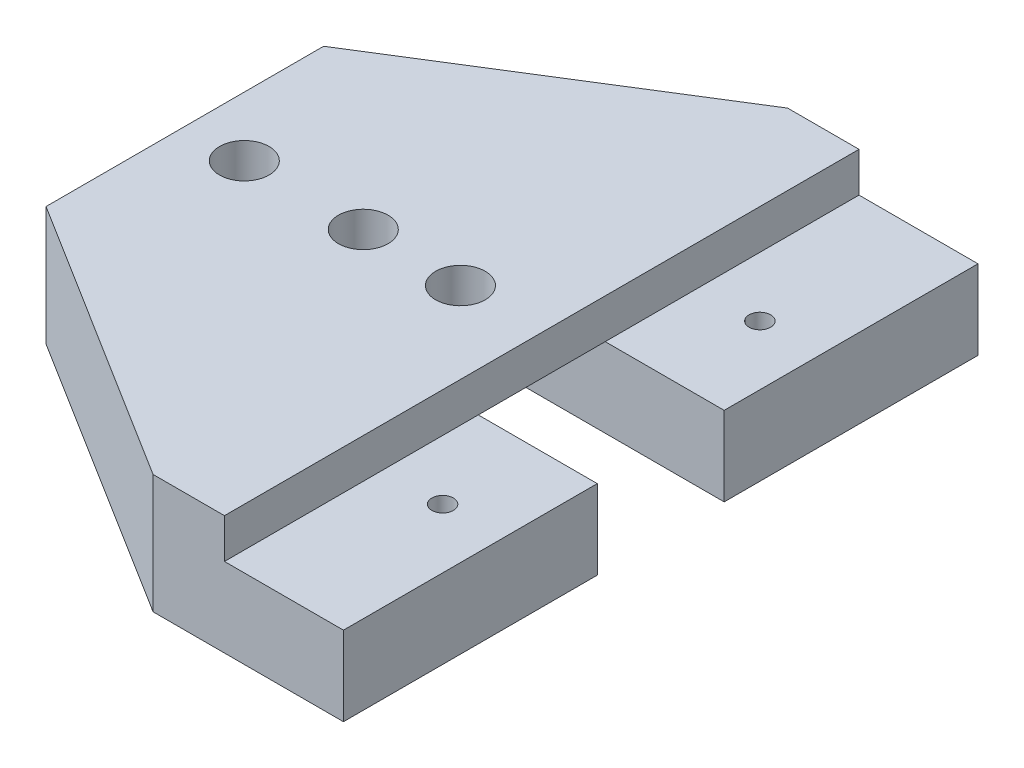
SolidWorks part; units mm, degrees
ref_plane "Front" through (0, 0, 0) normal (0, 0, 1) x (1, 0, 0)
ref_plane "Top" through (0, 0, 0) normal (0, 1, 0) x (1, 0, 0)
ref_plane "Right" through (0, 0, 0) normal (1, 0, 0) x (0, 0, -1)
sketch "Sketch1" plane through (0, 0, 0) normal (0, 1, 0) x (1, 0, 0)
  line L0 (-60.96, 22.225) -> (-60.96, -22.225)
  line L1 (-60.96, -22.225) -> (-15.24, -50.8)
  line L2 (-15.24, -50.8) -> (15.24, -50.8)
  line L3 (15.24, -50.8) -> (15.24, 50.8)
  line L4 (15.24, 50.8) -> (-15.24, 50.8)
  line L5 (-15.24, 50.8) -> (-60.96, 22.225)
  line L6 (-50, 0) -> (50, 0) construction
  line L7 (0, -50) -> (0, 50) construction
  point P6 (-60.96, 0)
  point P9 (15.24, 0)
  point P10 (0, 50.8)
  dimension "D1" = 76.2
  dimension "D2" = 101.6
  dimension "D3" = 44.45
  dimension "D4" = 30.48
extrude "Boss-Extrude1" add sketch "Sketch1" along normal mid plane 19.05 contours L3 L4 L5 L0 L1 L2
sketch "Sketch2" plane through (0, -9.525, 0) normal (0, -1, 0) x (1, 0, 0)
  line L0 (-60.96, -22.225) -> (-60.96, 22.225) construction
  line L1 (-60.96, -10.16) -> (15.24, -10.16)
  line L2 (-60.96, -10.16) -> (-60.96, 10.16)
  line L3 (-60.96, 10.16) -> (15.24, 10.16)
  line L4 (15.24, -10.16) -> (15.24, 10.16)
  line L5 (15.24, 50.8) -> (15.24, -50.8) construction
  line L6 (50, 0) -> (-50, 0) construction
  point P8 (15.24, 0)
  point P11 (8.3117, 28.5962)
  point P12 (8.3117, -19.4929)
  dimension "D1" = 20.32
extrude "Cut-Extrude1" cut sketch "Sketch2" against normal blind 12.7
sketch "Sketch3" plane through (0, 9.525, 0) normal (0, 1, 0) x (1, 0, 0)
  line L0 (15.24, 50.8) -> (-15.24, 50.8) construction
  line L1 (15.24, -50.8) -> (-3.81, -50.8)
  line L2 (15.24, -50.8) -> (15.24, 50.8)
  line L3 (15.24, 50.8) -> (-3.81, 50.8)
  line L4 (-3.81, -50.8) -> (-3.81, 50.8)
  dimension "D1" = 19.05
extrude "Cut-Extrude2" cut sketch "Sketch3" against normal blind 6.35 contours L4 L3 L2 L1
sketch "Sketch4" plane through (0, 9.525, 0) normal (0, 1, 0) x (1, 0, 0)
  line L0 (-50, 0) -> (50, 0) construction
  line L1 (-60.96, 22.225) -> (-60.96, -22.225) construction
  point P0 (-16.8275, 0)
  point P1 (-32.385, 0)
  point P4 (-51.435, 0)
  dimension "D1" = 19.05
  dimension "D2" = 9.525
  dimension "D3" = 15.5575
hole_wizard "5/16 (0.3125) Diameter Hole1" positions "Sketch5" profile "Sketch6" hole size "5/16" standard "ANSI Inch" end condition through all
sketch "Sketch5" plane through (0, 9.525, 0) normal (0, 1, 0) x (1, 0, 0)
  point P0 (-51.435, 0)
  point P3 (-32.385, 0)
  point P6 (-16.8275, 0)
sketch "Sketch6" plane through (-51.435, 9.525, 0) normal (1, 0, 0) x (0, 0, 1)
  line L0 (0, 0) -> (0, 19.05)
  line L1 (0, 19.05) -> (3.9687, 19.05)
  line L2 (3.9687, 19.05) -> (3.9687, 0)
  line L5 (3.9687, 0) -> (0, 0)
  line L11 (0, -6.35) -> (0, 107.95) construction
  dimension "Thru Hole Dia." = 7.9375
  dimension "Thru Hole Depth" = 19.05
sketch "Sketch7" plane through (0, -9.525, 0) normal (0, -1, 0) x (1, 0, 0)
  line L0 (5.715, 25.4) -> (5.715, -25.4) construction
  line L1 (50, 0) -> (-50, 0) construction
  line L2 (15.24, -10.16) -> (15.24, -50.8) construction
  point P0 (5.715, 25.4)
  point P1 (5.715, -25.4)
  point P4 (5.715, 0)
  dimension "D1" = 50.8
  dimension "D2" = 9.525
hole_wizard "#8-32 Tapped Hole1" positions "Sketch8" profile "Sketch10" tap size "#8-32" standard "ANSI Inch" end condition through all
sketch "Sketch8" plane through (0, -9.525, 0) normal (0, -1, 0) x (-1, 0, 0)
  point P0 (-5.715, -25.4)
  point P3 (-5.715, 25.4)
sketch "Sketch10" plane through (5.715, -9.525, 25.4) normal (1, 0, 0) x (0, 0, -1)
  line L0 (0, 0) -> (0, 19.05)
  line L1 (0, 19.05) -> (1.7272, 19.05)
  line L2 (1.7272, 19.05) -> (1.7272, 0)
  line L5 (1.7272, 0) -> (0, 0)
  line L11 (0, -6.35) -> (0, 107.95) construction
  dimension "Thru Tap Drill Dia." = 3.4544
  dimension "Thru Tap Drill Depth" = 19.05
cosmetic thread "Hole Thread1" parameters "D2"=4.1656
cosmetic thread "Hole Thread2" parameters "D2"=4.1656
